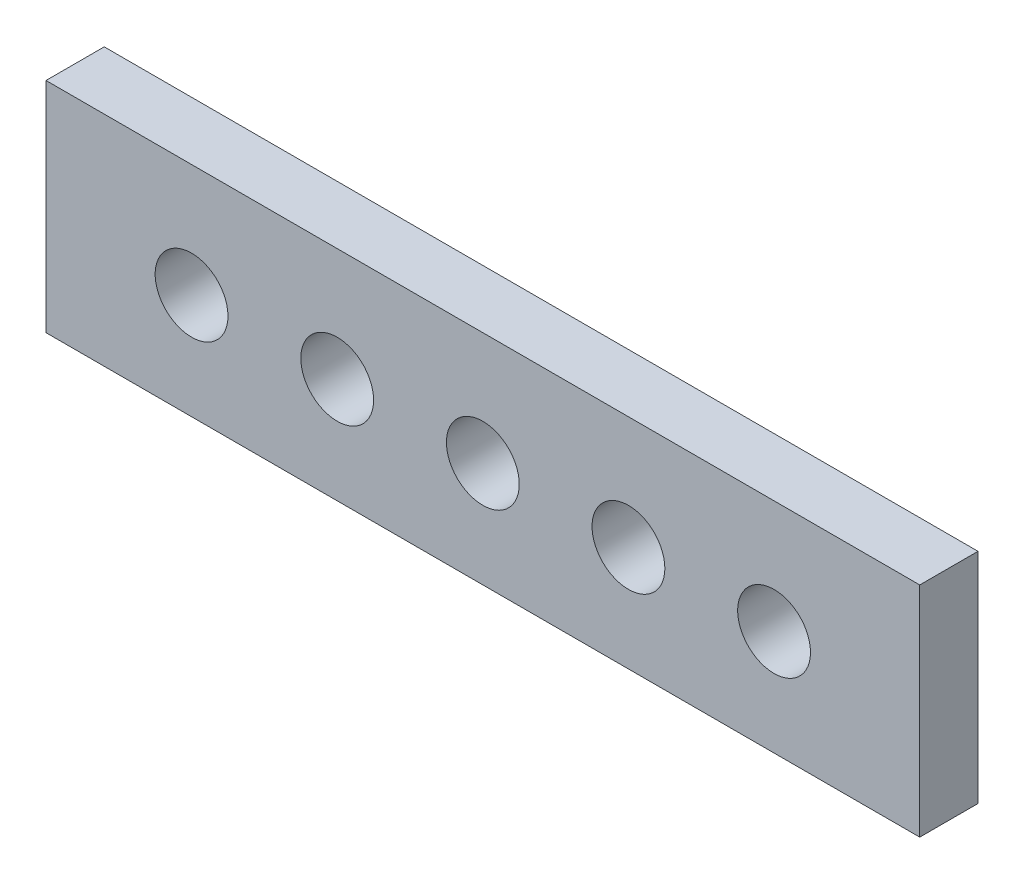
SolidWorks part; units mm, degrees
ref_plane "Front Plane" through (0, 0, 0) normal (0, 0, 1) x (1, 0, 0)
ref_plane "Top Plane" through (0, 0, 0) normal (0, 1, 0) x (1, 0, 0)
ref_plane "Right Plane" through (0, 0, 0) normal (1, 0, 0) x (0, 0, -1)
sketch "Sketch1" plane through (0, 0, 0) normal (0, 0, 1) x (1, 0, 0)
  line L1 (-43.694, 20.1839) -> (108.706, 20.1839)
  line L2 (-43.694, 20.1839) -> (-43.694, -17.9161)
  line L3 (-43.694, -17.9161) -> (108.706, -17.9161)
  line L4 (108.706, 20.1839) -> (108.706, -17.9161)
  circle A0 centre (-18.3032, 0.4519) radius 6.35
  circle A1 centre (32.4968, 0.4519) radius 6.35
  circle A2 centre (7.0968, 0.4519) radius 6.35
  circle A3 centre (57.8968, 0.4519) radius 6.35
  circle A4 centre (83.2968, 0.4519) radius 6.35
  point P6 (0, 0)
  point P9 (0, 0)
  point P10 (0, 0)
  point P17 (0, 0)
extrude "Boss-Extrude1" add sketch "Sketch1" along normal blind 10.16
